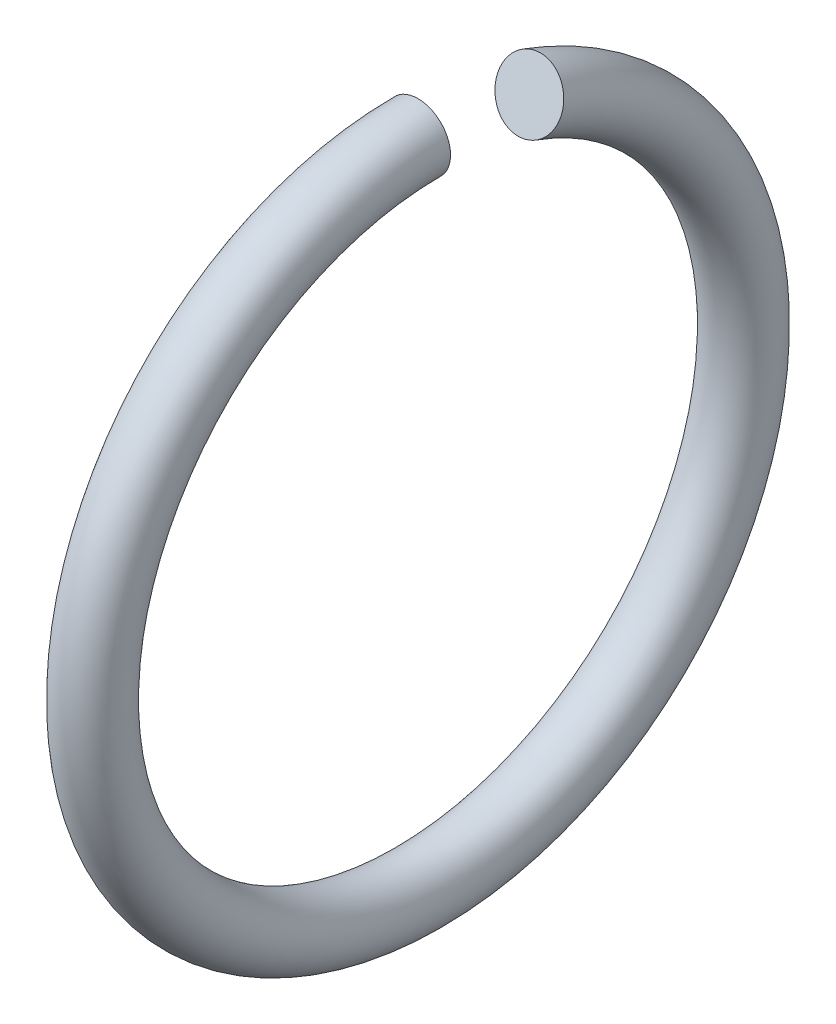
SolidWorks part; units mm, degrees
ref_plane "Face" through (0, 0, 0) normal (0, 0, 1) x (1, 0, 0)
ref_plane "Dessus" through (0, 0, 0) normal (0, 1, 0) x (1, 0, 0)
ref_plane "Droite" through (0, 0, 0) normal (1, 0, 0) x (0, 0, -1)
sketch "Esquisse1" plane through (0, 0, 0) normal (0, 0, 1) x (1, 0, 0)
  line L0 (-15.7703, 0) -> (43.6824, 0) construction
  circle A0 centre (0, 15) radius 1.5
  dimension "D1" = 3
  dimension "D2" = 15
revolve "Révolution1" add sketch "Esquisse1" angle 340 about L0
